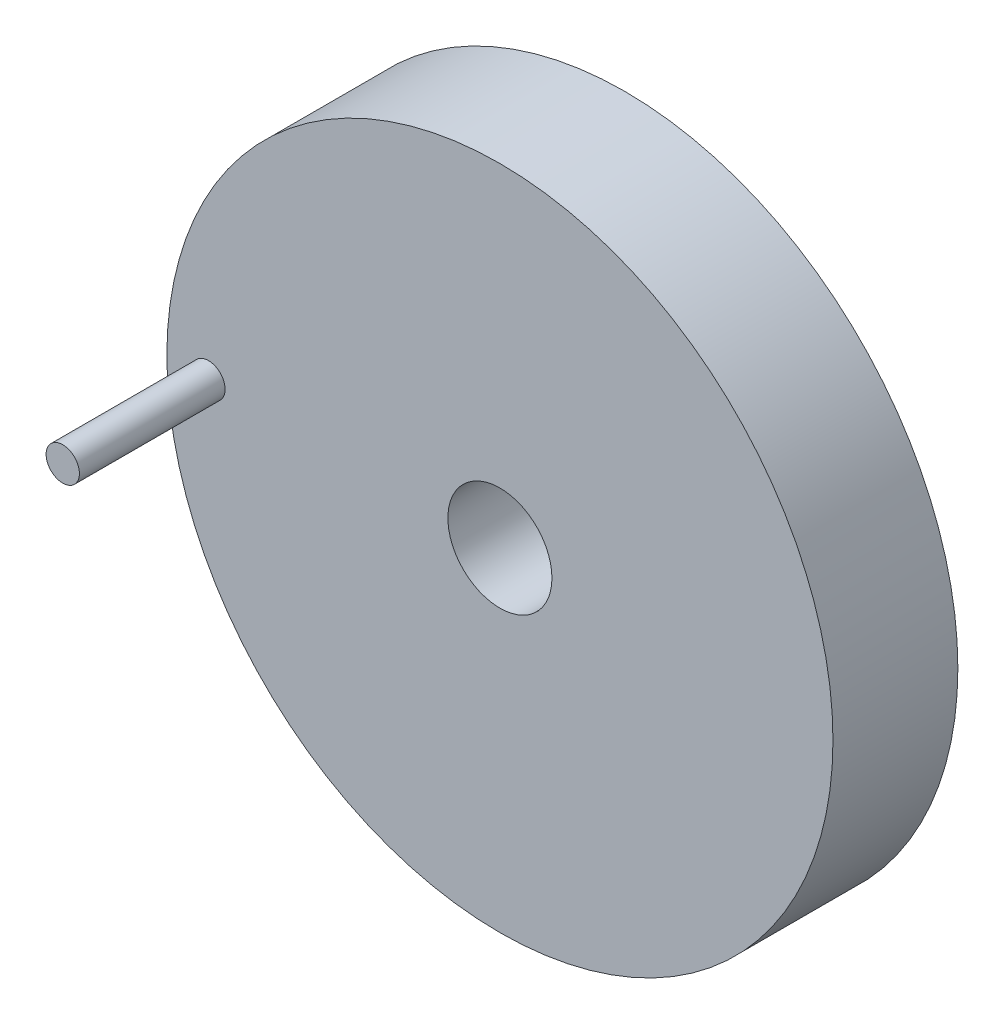
SolidWorks part; units mm, degrees
ref_plane "Front Plane" through (0, 0, 0) normal (0, 0, 1) x (1, 0, 0)
ref_plane "Top Plane" through (0, 0, 0) normal (0, 1, 0) x (1, 0, 0)
ref_plane "Right Plane" through (0, 0, 0) normal (1, 0, 0) x (0, 0, -1)
sketch "Sketch2" plane through (0, 0, 0) normal (0, 0, 1) x (1, 0, 0)
  circle A0 centre (0, 0) radius 80
  circle A1 centre (0, 0) radius 12.5
  dimension "D1" = 160
  dimension "D2" = 25
extrude "Boss-Extrude1" add sketch "Sketch2" against normal blind 30
sketch "Sketch3" plane through (0, 0, 0) normal (0, 0, 1) x (1, 0, 0)
  circle A0 centre (-70, 0) radius 4
  dimension "D1" = 8
  dimension "D2" = 70
extrude "Boss-Extrude2" add sketch "Sketch3" along normal blind 35
